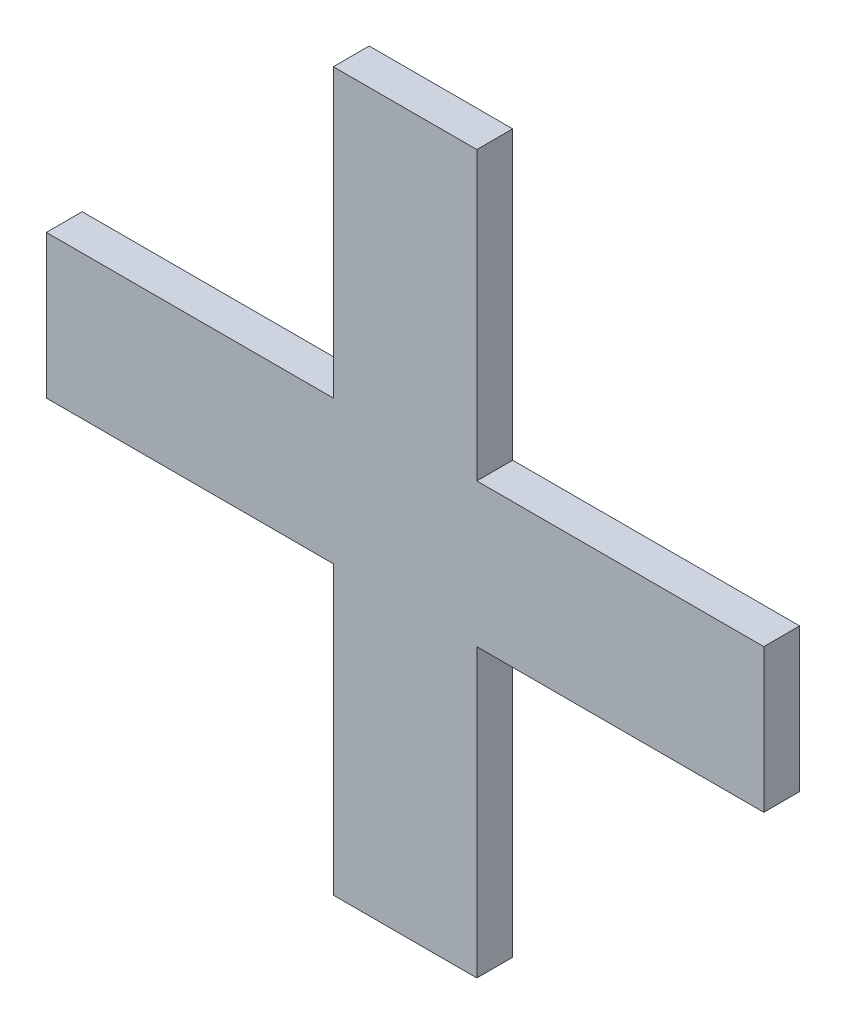
SolidWorks part; units mm, degrees
ref_plane "Front Plane" through (0, 0, 0) normal (0, 0, 1) x (1, 0, 0)
ref_plane "Top Plane" through (0, 0, 0) normal (0, 1, 0) x (1, 0, 0)
ref_plane "Right Plane" through (0, 0, 0) normal (1, 0, 0) x (0, 0, -1)
sketch "Sketch1" plane through (0, 0, 0) normal (0, 0, 1) x (1, 0, 0)
  line L0 (-6.35, 33.578) -> (6.35, 33.578)
  line L1 (6.35, 33.578) -> (6.35, 8.178)
  line L2 (6.35, 8.178) -> (31.75, 8.178)
  line L3 (31.75, 8.178) -> (31.75, -4.522)
  line L4 (31.75, -4.522) -> (6.35, -4.522)
  line L5 (6.35, -4.522) -> (6.35, -29.922)
  line L6 (6.35, -29.922) -> (-6.35, -29.922)
  line L7 (-6.35, -29.922) -> (-6.35, -4.522)
  line L8 (-6.35, -4.522) -> (-31.75, -4.522)
  line L9 (-31.75, -4.522) -> (-31.75, 8.178)
  line L10 (-31.75, 8.178) -> (-6.35, 8.178)
  line L11 (-6.35, 8.178) -> (-6.35, 33.578)
  point P2 (0, -29.922)
  point P13 (0, 33.578)
  dimension "D1" = 12.7
  dimension "D2" = 12.7
  dimension "D3" = 25.4
  dimension "D4" = 25.4
  dimension "D5" = 12.7
  dimension "D6" = 25.4
  dimension "D7" = 25.4
  dimension "D8" = 12.7
extrude "Boss-Extrude1" add sketch "Sketch1" along normal blind 3.175
